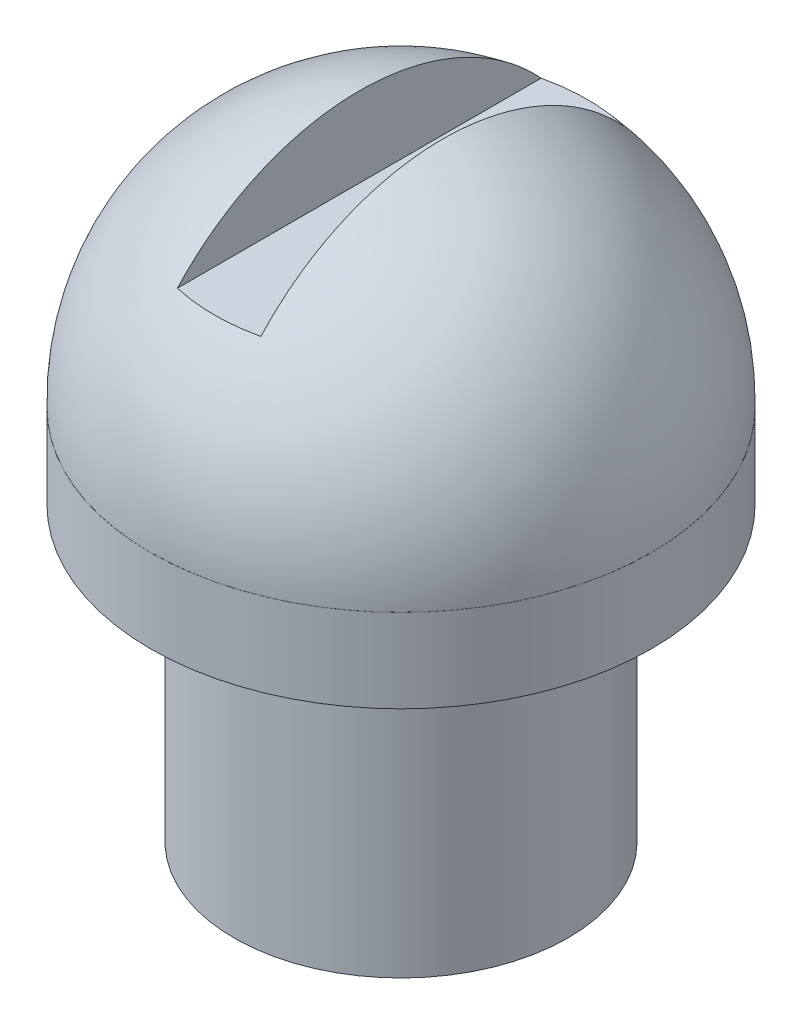
SolidWorks part; units mm, degrees
ref_plane "Front Plane" through (0, 0, 0) normal (0, 0, 1) x (1, 0, 0)
ref_plane "Top Plane" through (0, 0, 0) normal (0, 1, 0) x (1, 0, 0)
ref_plane "Right Plane" through (0, 0, 0) normal (1, 0, 0) x (0, 0, -1)
sketch "Sketch1" plane through (0, 0, 0) normal (0, 0, 1) x (1, 0, 0)
  line L0 (6, 10.4065) -> (5.9977, 10.4065)
  line L1 (0, 0.4065) -> (2, 0.4065)
  line L2 (2, 0.4065) -> (2, 1.4065)
  line L3 (2, 1.4065) -> (4, 1.4065)
  line L4 (4, 1.4065) -> (4, 8.4065)
  line L5 (4, 8.4065) -> (6, 8.4065)
  line L6 (6, 8.4065) -> (6, 10.4065)
  line L7 (0, 0.4065) -> (0, 16.5721)
  arc A0 (5.9977, 10.4065) -> (0, 16.5721) centre (0, 10.5721) ccw
revolve "Revolve1" add sketch "Sketch1" angle 360 about L7
sketch "Sketch2" plane through (0, 0, 0) normal (0, 0, 1) x (1, 0, 0)
  line L1 (-1, 18.5721) -> (1, 18.5721)
  line L2 (-1, 18.5721) -> (-1, 14.5721)
  line L3 (-1, 14.5721) -> (1, 14.5721)
  line L4 (1, 18.5721) -> (1, 14.5721)
  line L5 (-1, 18.5721) -> (1, 14.5721) construction
  line L6 (-1, 14.5721) -> (1, 18.5721) construction
  arc A0 (5.9977, 10.4065) -> (-5.9977, 10.4065) centre (0, 10.5721) ccw construction
  point P0 (0, 16.5721)
extrude "Cut-Extrude1" cut sketch "Sketch2" against normal mid plane 10
